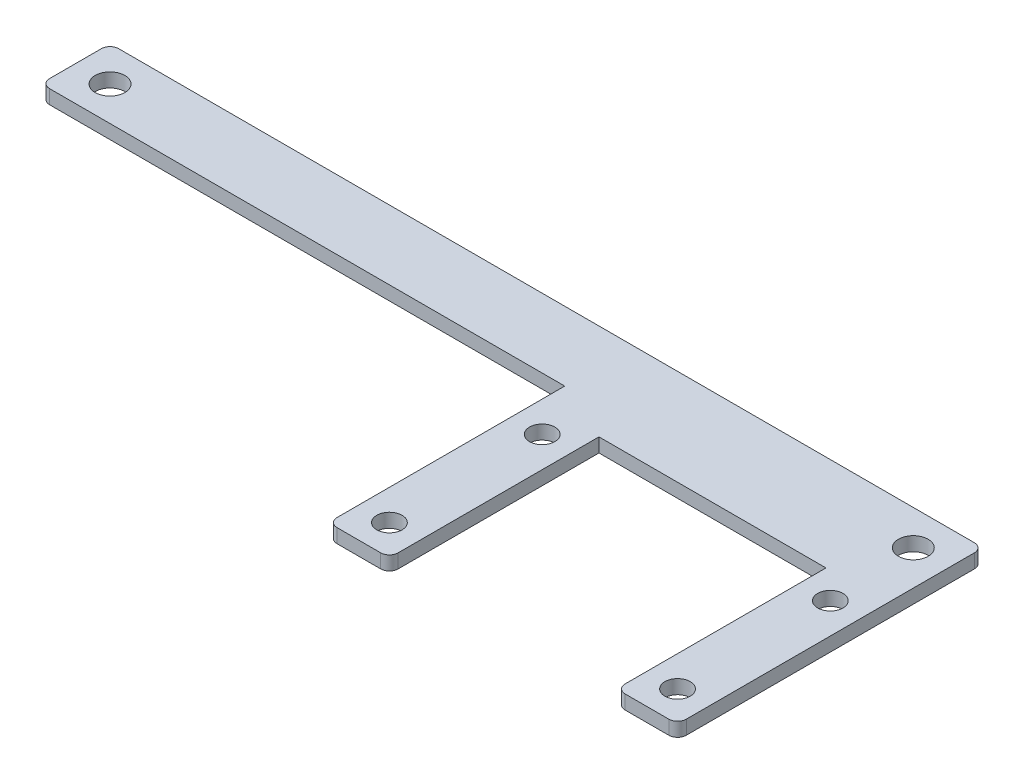
SolidWorks part; units mm, degrees
ref_plane "Front Plane" through (0, 0, 0) normal (0, 0, 1) x (1, 0, 0)
ref_plane "Top Plane" through (0, 0, 0) normal (0, 1, 0) x (1, 0, 0)
ref_plane "Right Plane" through (0, 0, 0) normal (1, 0, 0) x (0, 0, -1)
sketch "Sketch1" plane through (0, 0, 0) normal (0, 1, 0) x (1, 0, 0)
  line L1 (-20, -17.5) -> (20, -17.5)
  line L2 (-20, -17.5) -> (-20, 17.5)
  line L3 (-20, 17.5) -> (20, 17.5)
  line L4 (20, -17.5) -> (20, 17.5)
  line L5 (-20, -17.5) -> (20, 17.5) construction
  line L6 (-20, 17.5) -> (20, -17.5) construction
  point P0 (0, 0)
  dimension "D1" = 40
  dimension "D2" = 35
extrude "Boss-Extrude1" add sketch "Sketch1" along normal blind 1.6
sketch "Sketch2" plane through (0, 1.6, 0) normal (0, 1, 0) x (1, 0, 0)
  line L0 (0, 55.4269) -> (0, -17.5) construction
  line L1 (-20, -5.25) -> (-13, -5.25) construction
  line L2 (-16.5, -14) -> (16.5, -14) construction
  line L3 (-16.5, -14) -> (-16.5, 3.5) construction
  line L4 (-16.5, 3.5) -> (16.5, 3.5) construction
  line L5 (16.5, -14) -> (16.5, 3.5) construction
  line L6 (-16.5, -14) -> (16.5, 3.5) construction
  line L7 (-16.5, 3.5) -> (16.5, -14) construction
  line L8 (-13, -17.5) -> (13, -17.5)
  line L9 (-13, -17.5) -> (-13, 6.5)
  line L10 (-13, 6.5) -> (13, 6.5)
  line L11 (13, -17.5) -> (13, 6.5)
  line L12 (-20, -17.5) -> (20, -17.5) construction
  circle A0 centre (-16.5, 3.5) radius 1.45
  circle A1 centre (-16.5, -14) radius 1.45
  circle A2 centre (16.5, 3.5) radius 1.45
  circle A3 centre (16.5, -14) radius 1.45
  point P2 (0, -5.25)
  point P15 (0, 6.5)
  point P18 (-16.5, -5.25)
  point P19 (0, 0)
  point P20 (0, 0)
  point P21 (0, 2.4756)
  point P22 (-9.5097, 7.905)
  point P23 (0, 0)
  point P26 (0, -17.5)
  dimension "D4" = 2.9
  dimension "D1" = 33
  dimension "D2" = 26
  dimension "D3" = 24
  dimension "D5" = 17.5
  dimension "D6" = 3.5
extrude "Cut-Extrude1" cut sketch "Sketch2" against normal through all
sketch "Sketch4" plane through (0, 0, 0) normal (0, -1, 0) x (1, 0, 0)
  line L0 (20, 17.5) -> (20, -17.5) construction
  line L1 (-20, -17.5) -> (-80, -17.5)
  line L2 (-20, -17.5) -> (-20, -9.5789)
  line L3 (-20, -9.5789) -> (-80, -9.5789)
  line L4 (-80, -17.5) -> (-80, -9.5789)
  dimension "D1" = 100
extrude "Boss-Extrude2" add sketch "Sketch4" against normal up to surface (1.6 mm away) up to face at (16.5, 1.6, 15.45)
sketch "Sketch3" plane through (0, 1.6, 0) normal (0, 1, 0) x (1, 0, 0)
  line L0 (-80, 13.5) -> (20, 13.5) construction
  line L2 (20, -17.5) -> (20, 17.5) construction
  line L3 (16, 17.7542) -> (16, 13.5) construction
  line L4 (20, 17.5) -> (-80, 17.5) construction
  circle A0 centre (16, 13.5) radius 1.7
  circle A1 centre (-76, 13.5) radius 1.7
  dimension "D1" = 3.4
  dimension "D2" = 4
  dimension "D3" = 4
  dimension "D4" = 92
extrude "Cut-Extrude2" cut sketch "Sketch3" against normal through all
fillet "Fillet1" radius 1 7 edges at (20, 0.8, -17.5) (20, 0.8, 17.5) (13, 0.8, 17.5) (-13, 0.8, 17.5) (-20, 0.8, 17.5) (-80, 0.8, -17.5) (-80, 0.8, -9.5789)
